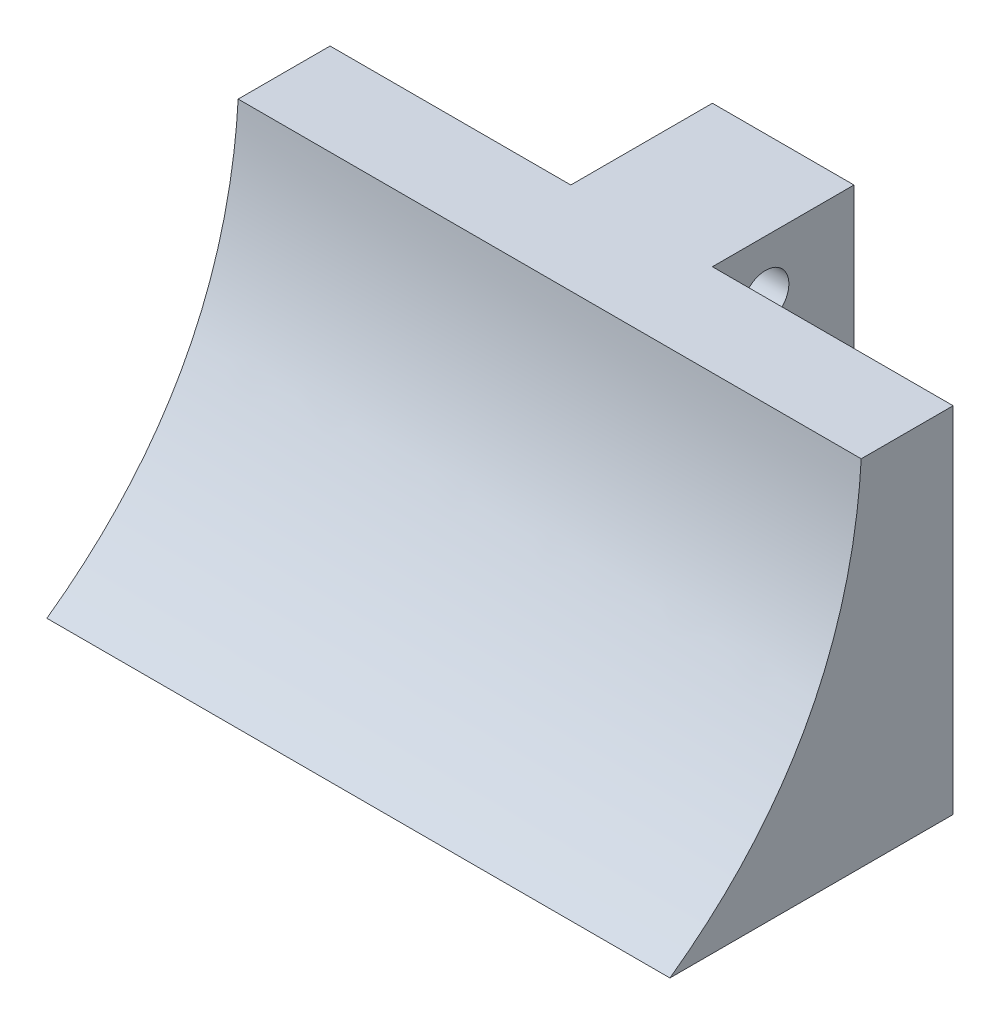
SolidWorks part; units mm, degrees
ref_plane "Front Plane" through (0, 0, 0) normal (0, 0, 1) x (1, 0, 0)
ref_plane "Top Plane" through (0, 0, 0) normal (0, 1, 0) x (1, 0, 0)
ref_plane "Right Plane" through (0, 0, 0) normal (1, 0, 0) x (0, 0, -1)
sketch "Sketch1" plane through (0, 0, 0) normal (0, 1, 0) x (1, 0, 0)
  line L0 (0, 0) -> (34, 0)
  line L1 (34, 0) -> (34, 20)
  line L2 (0, 0) -> (0, -40)
  line L3 (0, -40) -> (88, -40)
  line L4 (88, 0) -> (88, -40)
  line L5 (34, 20) -> (54, 20)
  line L6 (54, 20) -> (54, 0)
  line L7 (54, 0) -> (88, 0)
  dimension "D1" = 88
  dimension "D2" = 40
  dimension "D3" = 20
  dimension "D4" = 34
  dimension "D5" = 20
  dimension "D6" = 20
extrude "Boss-Extrude1" add sketch "Sketch1" along normal blind 50
ref_plane "Plane1" through (54, 0, 0) normal (1, 0, 0) x (0, 0, -1)
sketch "Sketch2" plane through (54, 0, 0) normal (1, 0, 0) x (0, 0, -1)
  line L0 (0, 50) -> (0, 0) construction
  line L1 (20, 0) -> (0, 0)
  line L2 (20, 0) -> (20, 15)
  line L3 (20, 15) -> (0, 15)
  line L4 (0, 0) -> (0, 15)
  dimension "D1" = 15
extrude "Cut-Extrude1" cut sketch "Sketch2" against normal blind 40
ref_plane "Plane2" through (88, 0, 0) normal (1, 0, 0) x (0, 0, -1)
sketch "Sketch3" plane through (88, 0, 0) normal (1, 0, 0) x (0, 0, -1)
  line L1 (-40, 50) -> (0, 50) construction
  line L5 (-40, 0) -> (-40, 50)
  line L6 (-40, 50) -> (-12.9805, 50)
  line L7 (-40, 0) -> (0, 0) construction
  spline S0 degree 2 poles (-40, 0) (-14.8301, 17.9787) (-12.9805, 50) knots 0 0 0 1 1 1
  dimension "D1" = 58.9335
  dimension "D2" = 16.7616
  dimension "D3" = 16.4929
extrude "Cut-Extrude2" cut sketch "Sketch3" against normal blind 134
sketch "Sketch5" plane through (54, 0, 0) normal (1, 0, 0) x (0, 0, -1)
  circle A0 centre (7.5, 42.5) radius 3.3
  circle A1 centre (7.5, 27.5) radius 3.3
  dimension "D5" = 6.6
  dimension "D6" = 6.6
extrude "Cut-Extrude3" cut sketch "Sketch5" against normal up to next
